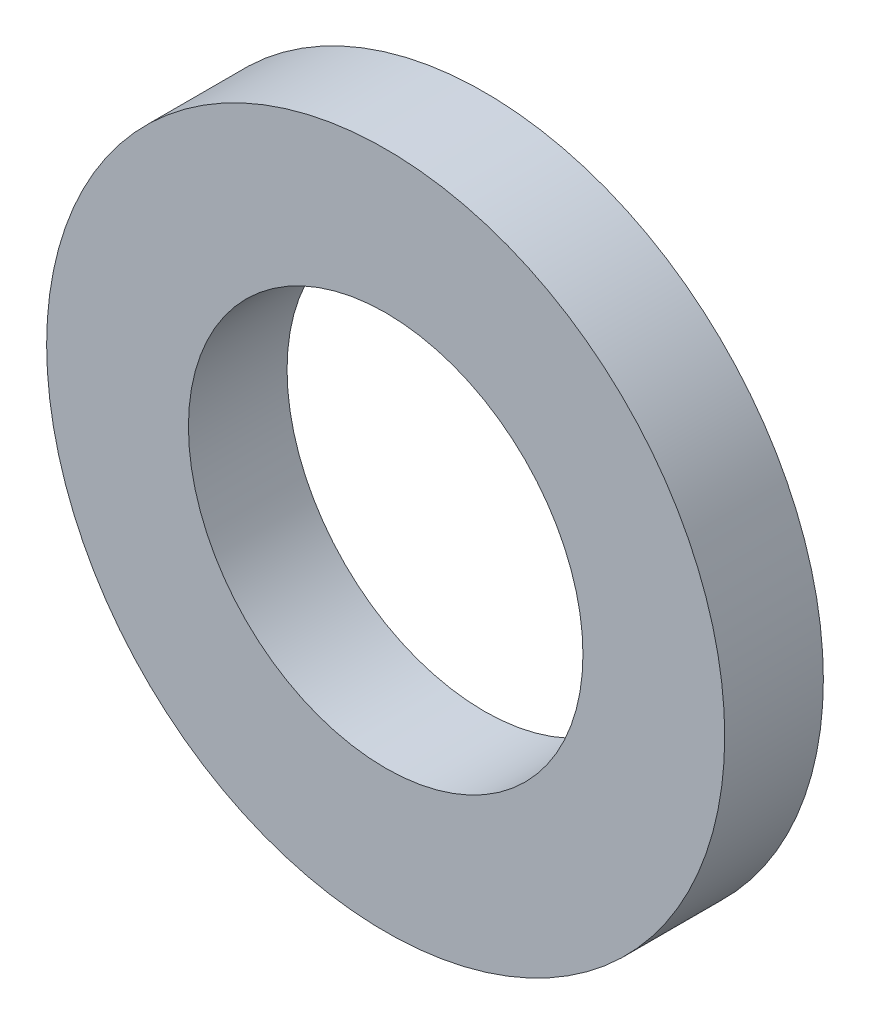
SolidWorks part; units mm, degrees
ref_plane "Top" through (0, 0, 0) normal (0, 0, 1) x (1, 0, 0)
ref_plane "Front" through (0, 0, 0) normal (0, 1, 0) x (1, 0, 0)
ref_plane "Right" through (0, 0, 0) normal (1, 0, 0) x (0, 0, -1)
sketch "Top Sketch" plane through (0, 0, 0) normal (0, 0, 1) x (1, 0, 0)
  circle A0 centre (0, 0) radius 3.2
  circle A1 centre (0, 0) radius 5.5
  dimension "Inside Diameter" = 6.4
  dimension "Outside Diameter" = 11
extrude "Extrude Thickness" add sketch "Top Sketch" along normal blind 1.6 contours A0
equation "\"M2 Close Fit Hole\"= 2.2"
equation "\"M2.5 Close Fit Hole\"= 2.7"
equation "\"M3 Close Fit Hole\"= 3.2"
equation "\"M4 Close Fit Hole\"= 4.3"
equation "\"M5 Close Fit Hole\"= 5.3"
equation "\"M6 Close Fit Hole\"= 6.3"
equation "\"M7 Close Fit Hole\"= 7.4"
equation "\"M8 Close Fit Hole\"= 8.4"
equation "\"M2 Tap Hole 75%\"= 1.6"
equation "\"M3 Tap Hole 75%\"= 2.5"
equation "\"M4 Tap Hole 75%\"= 3.3"
equation "\"M5 Tap Hole 75%\"= 4.2"
equation "\"M6 Tap Hole 75%\"= 5"
equation "\"M7 Tap Hole 75%\"= 6"
equation "\"M8 Tap Hole 75%\"= 6.8"
